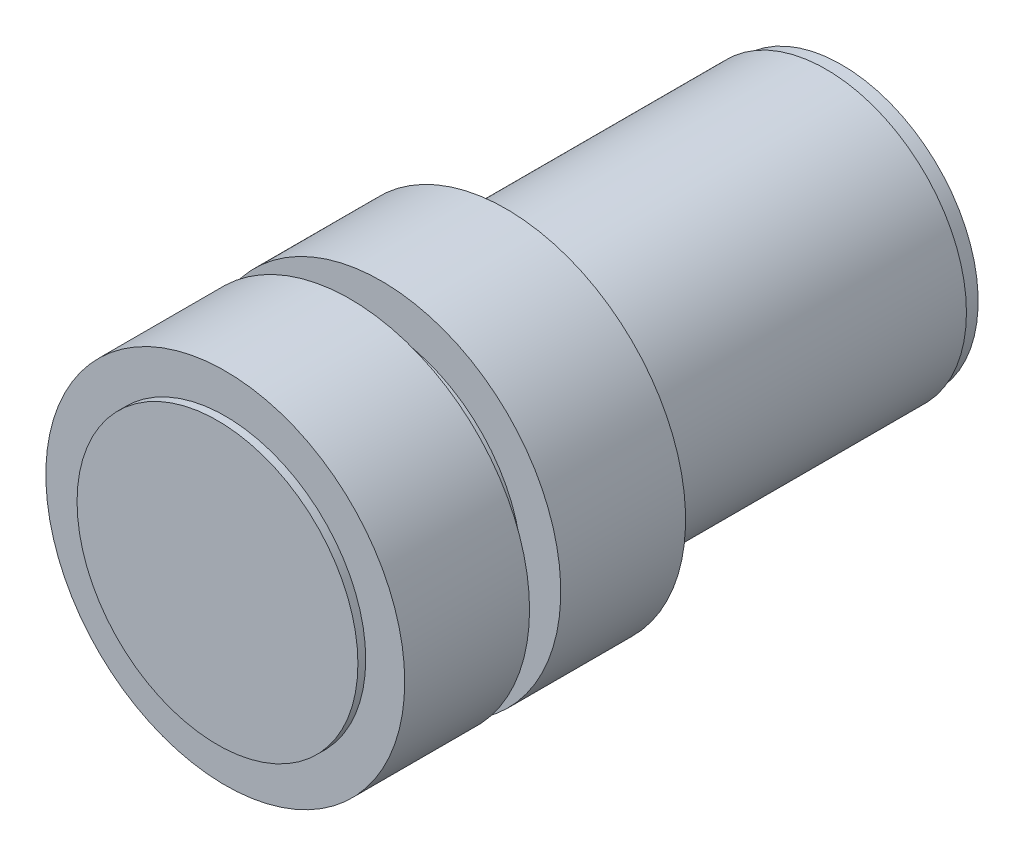
SolidWorks part; units mm, degrees
ref_plane "Front Plane" through (0, 0, 0) normal (0, 0, 1) x (1, 0, 0)
ref_plane "Top Plane" through (0, 0, 0) normal (0, 1, 0) x (1, 0, 0)
ref_plane "Right Plane" through (0, 0, 0) normal (1, 0, 0) x (0, 0, -1)
sketch "Sketch1" plane through (0, 0, 0) normal (0, 0, 1) x (1, 0, 0)
  circle A0 centre (0, 0) radius 9
  dimension "D1" = 18
extrude "Boss-Extrude1" add sketch "Sketch1" along normal blind 40
sketch "Sketch4" plane through (0, 0, 40) normal (0, 0, 1) x (1, 0, 0)
  circle A0 centre (0, 0) radius 11.5
  dimension "D1" = 23
extrude "Boss-Extrude5" add sketch "Sketch4" against normal blind 8 from offset 0.5 offset against normal yes
sketch "Sketch5" plane through (0, 0, 31.5) normal (0, 0, -1) x (-1, 0, 0)
  circle A0 centre (0, 0) radius 11.5
  circle A1 centre (0, 0) radius 11.5 construction
extrude "Boss-Extrude6" add sketch "Sketch5" along normal blind 8 from offset 2
sketch "Sketch6" plane through (0, 0, 0) normal (0, 0, -1) x (-1, 0, 0)
  circle A0 centre (0, 0) radius 8.75
  circle A1 centre (0, 0) radius 9 construction
  circle A2 centre (0, 0) radius 9
  dimension "D1" = 0.25
extrude "Cut-Extrude1" cut sketch "Sketch6" against normal blind 1
